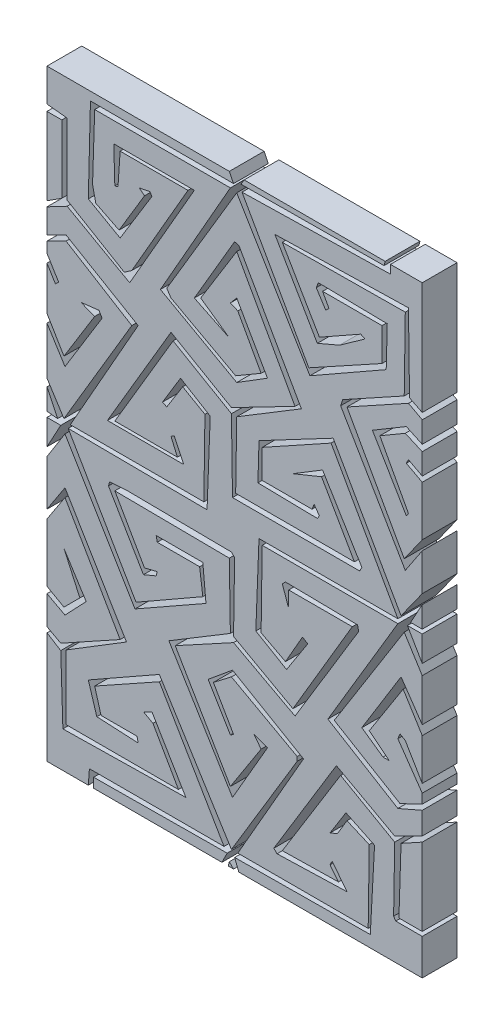
SolidWorks part; units mm, degrees
ref_plane "Front Plane" through (0, 0, 0) normal (0, 0, 1) x (1, 0, 0)
ref_plane "Top Plane" through (0, 0, 0) normal (0, 1, 0) x (1, 0, 0)
ref_plane "Right Plane" through (0, 0, 0) normal (1, 0, 0) x (0, 0, -1)
sketch "Sketch1" plane through (0, 0, 0) normal (0, 0, 1) x (1, 0, 0)
  line L0 (13.9275, -25.2817) -> (13.8361, -25.6475)
  line L1 (13.8361, -25.6475) -> (14.2933, -25.6475)
  line L2 (14.2933, -25.6475) -> (13.9275, -25.2817)
  line L3 (2.2224, -25.6475) -> (13.2874, -25.6475)
  line L4 (13.2874, -25.6475) -> (13.7446, -24.733)
  line L5 (13.7446, -24.733) -> (2.2224, -24.8245)
  line L6 (2.2224, -24.8245) -> (2.2224, -25.6475)
  line L7 (30.5707, -15.497) -> (28.7418, -16.5029)
  line L8 (28.7418, -16.5029) -> (28.5589, -22.1725)
  line L9 (28.5589, -22.1725) -> (30.5707, -22.1725)
  line L10 (30.5707, -22.1725) -> (30.5707, -15.497)
  line L11 (-0.2467, -5.1635) -> (-1.8012, -7.5411)
  line L12 (-1.8012, -7.5411) -> (-1.8012, -12.5707)
  line L13 (-1.8012, -12.5707) -> (-0.3381, -13.3937)
  line L14 (-0.3381, -13.3937) -> (1.0336, -12.022)
  line L15 (1.0336, -12.022) -> (-0.3381, -9.0043)
  line L16 (-0.3381, -9.0043) -> (1.5823, -12.022)
  line L17 (1.5823, -12.022) -> (-0.2467, -13.9424)
  line L18 (-0.2467, -13.9424) -> (-1.8012, -13.1194)
  line L19 (-1.8012, -13.1194) -> (-1.8012, -15.5884)
  line L20 (-1.8012, -15.5884) -> (-0.6124, -16.2285)
  line L21 (-0.6124, -16.2285) -> (4.5085, -13.3937)
  line L22 (4.5085, -13.3937) -> (-0.2467, -5.1635)
  line L23 (29.0161, -0.5912) -> (22.9807, -10.1931)
  line L24 (22.9807, -10.1931) -> (28.6503, -13.5766)
  line L25 (28.6503, -13.5766) -> (30.5707, -12.6621)
  line L26 (30.5707, -12.6621) -> (30.5707, -11.8391)
  line L27 (30.5707, -11.8391) -> (28.4675, -8.8214)
  line L28 (28.4675, -8.8214) -> (28.6503, -8.3642)
  line L29 (28.6503, -8.3642) -> (29.1076, -8.6385)
  line L30 (29.1076, -8.6385) -> (30.5707, -11.1075)
  line L31 (30.5707, -11.1075) -> (30.5707, -7.5411)
  line L32 (30.5707, -7.5411) -> (28.9247, -4.8892)
  line L33 (28.9247, -4.8892) -> (25.9984, -9.4615)
  line L34 (25.9984, -9.4615) -> (27.7359, -10.8332)
  line L35 (27.7359, -10.8332) -> (27.1872, -10.8332)
  line L36 (27.1872, -10.8332) -> (25.3583, -9.553)
  line L37 (25.3583, -9.553) -> (28.7418, -4.0662)
  line L38 (28.7418, -4.0662) -> (30.5707, -6.7181)
  line L39 (30.5707, -6.7181) -> (30.5707, -3.0603)
  line L40 (30.5707, -3.0603) -> (29.0161, -0.5912)
  line L41 (29.2905, 0.0489) -> (30.5707, -2.1458)
  line L42 (30.5707, -2.1458) -> (30.5707, 0.0489)
  line L43 (30.5707, 0.0489) -> (29.2905, 0.0489)
  line L44 (-0.6124, 0.0489) -> (-1.8012, 0.0489)
  line L45 (-1.8012, 0.0489) -> (-1.8012, -2.1458)
  line L46 (-1.8012, -2.1458) -> (-0.6124, 0.0489)
  line L47 (30.5707, 2.2436) -> (29.5648, 0.4147)
  line L48 (29.5648, 0.4147) -> (30.5707, 0.4147)
  line L49 (30.5707, 0.4147) -> (30.5707, 2.2436)
  line L50 (-1.8012, 2.335) -> (-1.8012, 0.5061)
  line L51 (-1.8012, 0.5061) -> (-0.8868, 0.4147)
  line L52 (-0.8868, 0.4147) -> (-1.8012, 2.335)
  line L53 (-0.1552, 14.0402) -> (-1.8012, 13.2171)
  line L54 (-1.8012, 13.2171) -> (-1.8012, 12.3027)
  line L55 (-1.8012, 12.3027) -> (-0.7953, 10.6567)
  line L56 (-0.7953, 10.6567) -> (-1.0697, 10.3823)
  line L57 (-1.0697, 10.3823) -> (-1.8012, 11.5711)
  line L58 (-1.8012, 11.5711) -> (-1.8012, 7.8218)
  line L59 (-1.8012, 7.8218) -> (-0.3381, 5.3528)
  line L60 (-0.3381, 5.3528) -> (2.3138, 9.6507)
  line L61 (2.3138, 9.6507) -> (1.125, 10.108)
  line L62 (1.125, 10.108) -> (2.6796, 10.2909)
  line L63 (2.6796, 10.2909) -> (2.954, 9.8336)
  line L64 (2.954, 9.8336) -> (-0.2467, 4.6212)
  line L65 (-0.2467, 4.6212) -> (-1.8012, 7.0903)
  line L66 (-1.8012, 7.0903) -> (-1.8012, 2.9752)
  line L67 (-1.8012, 2.9752) -> (-0.3381, 0.689)
  line L68 (-0.3381, 0.689) -> (5.5145, 10.5652)
  line L69 (5.5145, 10.5652) -> (-0.1552, 14.0402)
  line L70 (29.3819, 16.6921) -> (24.078, 13.7658)
  line L71 (24.078, 13.7658) -> (29.0161, 4.8955)
  line L72 (29.0161, 4.8955) -> (30.5707, 7.0903)
  line L73 (30.5707, 7.0903) -> (30.5707, 11.3882)
  line L74 (30.5707, 11.3882) -> (29.199, 12.1198)
  line L75 (29.199, 12.1198) -> (29.3819, 12.4856)
  line L76 (29.3819, 12.4856) -> (30.5707, 11.8455)
  line L77 (30.5707, 11.8455) -> (30.5707, 13.6744)
  line L78 (30.5707, 13.6744) -> (29.1076, 14.3145)
  line L79 (29.1076, 14.3145) -> (26.9129, 13.0343)
  line L80 (26.9129, 13.0343) -> (29.3819, 8.4619)
  line L81 (29.3819, 8.4619) -> (29.199, 8.1876)
  line L82 (29.199, 8.1876) -> (26.2727, 13.1257)
  line L83 (26.2727, 13.1257) -> (29.199, 14.8632)
  line L84 (29.199, 14.8632) -> (30.5707, 14.2231)
  line L85 (30.5707, 14.2231) -> (30.5707, 16.052)
  line L86 (30.5707, 16.052) -> (29.3819, 16.6921)
  line L87 (-0.521, 22.9104) -> (-1.8012, 22.9104)
  line L88 (-1.8012, 22.9104) -> (-1.8012, 16.2349)
  line L89 (-1.8012, 16.2349) -> (-0.521, 17.0579)
  line L90 (-0.521, 17.0579) -> (-0.521, 22.9104)
  line L91 (14.9334, 25.8367) -> (27.2787, 25.9282)
  line L92 (27.2787, 25.9282) -> (27.3701, 26.294)
  line L93 (27.3701, 26.294) -> (15.2077, 26.294)
  line L94 (15.2077, 26.294) -> (14.9334, 25.8367)
  line L95 (-1.8012, 26.294) -> (-1.8012, 23.4591)
  line L96 (-1.8012, 23.4591) -> (-0.0638, 23.2762)
  line L97 (-0.0638, 23.2762) -> (-0.0638, 17.1493)
  line L98 (-0.0638, 17.1493) -> (4.8743, 14.2231)
  line L99 (4.8743, 14.2231) -> (5.5145, 14.6803)
  line L100 (5.5145, 14.6803) -> (10.3611, 23.0933)
  line L101 (10.3611, 23.0933) -> (4.5085, 23.0933)
  line L102 (4.5085, 23.0933) -> (4.3256, 20.35)
  line L103 (4.3256, 20.35) -> (4.0513, 20.2585)
  line L104 (4.0513, 20.2585) -> (3.9599, 23.3677)
  line L105 (3.9599, 23.3677) -> (10.9098, 23.3677)
  line L106 (10.9098, 23.3677) -> (5.3316, 13.6744)
  line L107 (5.3316, 13.6744) -> (-0.0638, 16.6921)
  line L108 (-0.0638, 16.6921) -> (-1.8012, 15.7776)
  line L109 (-1.8012, 15.7776) -> (-1.8012, 13.6744)
  line L110 (-1.8012, 13.6744) -> (-0.1552, 14.4974)
  line L111 (-0.1552, 14.4974) -> (6.0631, 10.8395)
  line L112 (6.0631, 10.8395) -> (0.2106, 0.5061)
  line L113 (0.2106, 0.5061) -> (11.7328, 0.5061)
  line L114 (11.7328, 0.5061) -> (11.8242, 7.0903)
  line L115 (11.8242, 7.0903) -> (9.9039, 8.1876)
  line L116 (9.9039, 8.1876) -> (8.5322, 5.9929)
  line L117 (8.5322, 5.9929) -> (8.1664, 6.1758)
  line L118 (8.1664, 6.1758) -> (9.721, 8.7363)
  line L119 (9.721, 8.7363) -> (12.2815, 7.1817)
  line L120 (12.2815, 7.1817) -> (12.0071, 0.0489)
  line L121 (12.0071, 0.0489) -> (0.0277, 0.1403)
  line L122 (0.0277, 0.1403) -> (5.8802, -9.9187)
  line L123 (5.8802, -9.9187) -> (11.6413, -6.6267)
  line L124 (11.6413, -6.6267) -> (11.367, -4.5234)
  line L125 (11.367, -4.5234) -> (7.7092, -4.5234)
  line L126 (7.7092, -4.5234) -> (7.6177, -4.0662)
  line L127 (7.6177, -4.0662) -> (11.6413, -4.0662)
  line L128 (11.6413, -4.0662) -> (11.9157, -6.9925)
  line L129 (11.9157, -6.9925) -> (5.7888, -10.4674)
  line L130 (5.7888, -10.4674) -> (-0.2467, -0.4083)
  line L131 (-0.2467, -0.4083) -> (-1.8012, -2.8774)
  line L132 (-1.8012, -2.8774) -> (-1.8012, -6.8096)
  line L133 (-1.8012, -6.8096) -> (-0.2467, -4.432)
  line L134 (-0.2467, -4.432) -> (5.0572, -13.3023)
  line L135 (5.0572, -13.3023) -> (-0.1552, -16.5029)
  line L136 (-0.1552, -16.5029) -> (-0.1552, -22.0811)
  line L137 (-0.1552, -22.0811) -> (9.5381, -22.0811)
  line L138 (9.5381, -22.0811) -> (7.3434, -18.2404)
  line L139 (7.3434, -18.2404) -> (6.5204, -17.7831)
  line L140 (6.5204, -17.7831) -> (7.2519, -17.4173)
  line L141 (7.2519, -17.4173) -> (10.1782, -22.3554)
  line L142 (10.1782, -22.3554) -> (-0.4296, -22.5383)
  line L143 (-0.4296, -22.5383) -> (-0.6124, -16.7772)
  line L144 (-0.6124, -16.7772) -> (-1.8012, -16.0456)
  line L145 (-1.8012, -16.0456) -> (-1.8012, -25.6475)
  line L146 (-1.8012, -25.6475) -> (1.7652, -25.6475)
  line L147 (1.7652, -25.6475) -> (1.8566, -24.3672)
  line L148 (1.8566, -24.3672) -> (13.4703, -24.3672)
  line L149 (13.4703, -24.3672) -> (7.8921, -14.8568)
  line L150 (7.8921, -14.8568) -> (2.3138, -17.966)
  line L151 (2.3138, -17.966) -> (2.8625, -19.8864)
  line L152 (2.8625, -19.8864) -> (5.9717, -19.8864)
  line L153 (5.9717, -19.8864) -> (6.0631, -20.3436)
  line L154 (6.0631, -20.3436) -> (2.4967, -20.1607)
  line L155 (2.4967, -20.1607) -> (1.7652, -17.7831)
  line L156 (1.7652, -17.7831) -> (7.8921, -14.3082)
  line L157 (7.8921, -14.3082) -> (14.1104, -24.2758)
  line L158 (14.1104, -24.2758) -> (19.7801, -14.8568)
  line L159 (19.7801, -14.8568) -> (19.7801, -14.4911)
  line L160 (19.7801, -14.4911) -> (14.1104, -11.3819)
  line L161 (14.1104, -11.3819) -> (12.5558, -12.5707)
  line L162 (12.5558, -12.5707) -> (14.2933, -15.5884)
  line L163 (14.2933, -15.5884) -> (14.0189, -15.7713)
  line L164 (14.0189, -15.7713) -> (12.0986, -12.5707)
  line L165 (12.0986, -12.5707) -> (14.2018, -10.8332)
  line L166 (14.2018, -10.8332) -> (20.3287, -14.3996)
  line L167 (20.3287, -14.3996) -> (14.6591, -24.2758)
  line L168 (14.6591, -24.2758) -> (25.907, -24.2758)
  line L169 (25.907, -24.2758) -> (25.9984, -17.966)
  line L170 (25.9984, -17.966) -> (24.078, -17.143)
  line L171 (24.078, -17.143) -> (23.255, -18.5147)
  line L172 (23.255, -18.5147) -> (22.6149, -18.789)
  line L173 (22.6149, -18.789) -> (23.9866, -16.5943)
  line L174 (23.9866, -16.5943) -> (26.4556, -17.7831)
  line L175 (26.4556, -17.7831) -> (26.0898, -24.6416)
  line L176 (26.0898, -24.6416) -> (14.3847, -24.733)
  line L177 (14.3847, -24.733) -> (14.7505, -25.6475)
  line L178 (14.7505, -25.6475) -> (30.5707, -25.6475)
  line L179 (30.5707, -25.6475) -> (30.5707, -22.5383)
  line L180 (30.5707, -22.5383) -> (28.2846, -22.5383)
  line L181 (28.2846, -22.5383) -> (28.1017, -22.264)
  line L182 (28.1017, -22.264) -> (28.1931, -16.6858)
  line L183 (28.1931, -16.6858) -> (23.5294, -14.0338)
  line L184 (23.5294, -14.0338) -> (18.4998, -22.1725)
  line L185 (18.4998, -22.1725) -> (23.3465, -22.0811)
  line L186 (23.3465, -22.0811) -> (22.6149, -21.1666)
  line L187 (22.6149, -21.1666) -> (22.7978, -20.8008)
  line L188 (22.7978, -20.8008) -> (24.078, -22.4469)
  line L189 (24.078, -22.4469) -> (18.0426, -22.6298)
  line L190 (18.0426, -22.6298) -> (17.7682, -22.3554)
  line L191 (17.7682, -22.3554) -> (23.1636, -13.4851)
  line L192 (23.1636, -13.4851) -> (28.1931, -16.2285)
  line L193 (28.1931, -16.2285) -> (30.5707, -15.0397)
  line L194 (30.5707, -15.0397) -> (30.5707, -13.1194)
  line L195 (30.5707, -13.1194) -> (28.4675, -14.0338)
  line L196 (28.4675, -14.0338) -> (22.432, -10.376)
  line L197 (22.432, -10.376) -> (28.4675, -0.2254)
  line L198 (28.4675, -0.2254) -> (16.7623, -0.2254)
  line L199 (16.7623, -0.2254) -> (16.6709, -6.8096)
  line L200 (16.6709, -6.8096) -> (18.7742, -7.9069)
  line L201 (18.7742, -7.9069) -> (20.2373, -5.3464)
  line L202 (20.2373, -5.3464) -> (20.6945, -5.6208)
  line L203 (20.6945, -5.6208) -> (18.8656, -8.4556)
  line L204 (18.8656, -8.4556) -> (16.2137, -6.901)
  line L205 (16.2137, -6.901) -> (16.488, 0.1403)
  line L206 (16.488, 0.1403) -> (28.4675, 0.1403)
  line L207 (28.4675, 0.1403) -> (22.7063, 10.3823)
  line L208 (22.7063, 10.3823) -> (16.7623, 7.0903)
  line L209 (16.7623, 7.0903) -> (16.7623, 4.6212)
  line L210 (16.7623, 4.6212) -> (21.0603, 4.6212)
  line L211 (21.0603, 4.6212) -> (21.2432, 5.0784)
  line L212 (21.2432, 5.0784) -> (21.7004, 4.4383)
  line L213 (21.7004, 4.4383) -> (21.5175, 4.164)
  line L214 (21.5175, 4.164) -> (16.3966, 4.2554)
  line L215 (16.3966, 4.2554) -> (16.488, 7.456)
  line L216 (16.488, 7.456) -> (22.8892, 10.8395)
  line L217 (22.8892, 10.8395) -> (28.7418, 0.5061)
  line L218 (28.7418, 0.5061) -> (30.5707, 3.0666)
  line L219 (30.5707, 3.0666) -> (30.5707, 6.2672)
  line L220 (30.5707, 6.2672) -> (29.1076, 4.0725)
  line L221 (29.1076, 4.0725) -> (23.5294, 13.5829)
  line L222 (23.5294, 13.5829) -> (23.7122, 14.1316)
  line L223 (23.7122, 14.1316) -> (29.0161, 17.0579)
  line L224 (29.0161, 17.0579) -> (29.1076, 23.3677)
  line L225 (29.1076, 23.3677) -> (18.4998, 23.2762)
  line L226 (18.4998, 23.2762) -> (21.7004, 17.7895)
  line L227 (21.7004, 17.7895) -> (25.2668, 19.8013)
  line L228 (25.2668, 19.8013) -> (25.6326, 19.6184)
  line L229 (25.6326, 19.6184) -> (23.4379, 18.0638)
  line L230 (23.4379, 18.0638) -> (21.5175, 17.2408)
  line L231 (21.5175, 17.2408) -> (17.8597, 23.5506)
  line L232 (17.8597, 23.5506) -> (29.3819, 23.8249)
  line L233 (29.3819, 23.8249) -> (29.4734, 17.1493)
  line L234 (29.4734, 17.1493) -> (30.5707, 16.6007)
  line L235 (30.5707, 16.6007) -> (30.5707, 26.294)
  line L236 (30.5707, 26.294) -> (27.8273, 26.294)
  line L237 (27.8273, 26.294) -> (27.8273, 25.5624)
  line L238 (27.8273, 25.5624) -> (15.0249, 25.288)
  line L239 (15.0249, 25.288) -> (20.786, 15.0461)
  line L240 (20.786, 15.0461) -> (27.0958, 18.521)
  line L241 (27.0958, 18.521) -> (27.0958, 21.3559)
  line L242 (27.0958, 21.3559) -> (21.9748, 21.3559)
  line L243 (21.9748, 21.3559) -> (22.5234, 20.35)
  line L244 (22.5234, 20.35) -> (22.2491, 20.0756)
  line L245 (22.2491, 20.0756) -> (21.4261, 21.3559)
  line L246 (21.4261, 21.3559) -> (21.609, 21.8131)
  line L247 (21.609, 21.8131) -> (27.553, 21.7216)
  line L248 (27.553, 21.7216) -> (27.4615, 18.2467)
  line L249 (27.4615, 18.2467) -> (20.8774, 14.4974)
  line L250 (20.8774, 14.4974) -> (14.5676, 25.0137)
  line L251 (14.5676, 25.0137) -> (8.5322, 14.8632)
  line L252 (8.5322, 14.8632) -> (8.898, 14.3145)
  line L253 (8.898, 14.3145) -> (14.4762, 11.2968)
  line L254 (14.4762, 11.2968) -> (16.6709, 12.577)
  line L255 (16.6709, 12.577) -> (14.6591, 16.2349)
  line L256 (14.6591, 16.2349) -> (14.0189, 16.5092)
  line L257 (14.0189, 16.5092) -> (14.5676, 17.1493)
  line L258 (14.5676, 17.1493) -> (17.2196, 12.4856)
  line L259 (17.2196, 12.4856) -> (14.5676, 10.8395)
  line L260 (14.5676, 10.8395) -> (7.9835, 14.4974)
  line L261 (7.9835, 14.4974) -> (14.0189, 25.1052)
  line L262 (14.0189, 25.1052) -> (2.3138, 25.1052)
  line L263 (2.3138, 25.1052) -> (2.1309, 19.4355)
  line L264 (2.1309, 19.4355) -> (2.4053, 18.1552)
  line L265 (2.4053, 18.1552) -> (4.4171, 17.1493)
  line L266 (4.4171, 17.1493) -> (6.6118, 20.8072)
  line L267 (6.6118, 20.8072) -> (6.1546, 21.173)
  line L268 (6.1546, 21.173) -> (7.069, 21.3559)
  line L269 (7.069, 21.3559) -> (7.2519, 21.0815)
  line L270 (7.2519, 21.0815) -> (4.5085, 16.6007)
  line L271 (4.5085, 16.6007) -> (1.7652, 18.1552)
  line L272 (1.7652, 18.1552) -> (1.948, 25.5624)
  line L273 (1.948, 25.5624) -> (14.2933, 25.5624)
  line L274 (14.2933, 25.5624) -> (13.9275, 26.294)
  line L275 (13.9275, 26.294) -> (-1.8012, 26.294)
  line L276 (24.9925, -2.0544) -> (25.0839, -2.5116)
  line L277 (25.0839, -2.5116) -> (19.5972, -11.5648)
  line L278 (19.5972, -11.5648) -> (14.2933, -8.7299)
  line L279 (14.2933, -8.7299) -> (9.2637, -11.4733)
  line L280 (9.2637, -11.4733) -> (14.0189, -19.612)
  line L281 (14.0189, -19.612) -> (16.6709, -15.497)
  line L282 (16.6709, -15.497) -> (16.0308, -14.6739)
  line L283 (16.0308, -14.6739) -> (17.2196, -15.1312)
  line L284 (17.2196, -15.1312) -> (14.2018, -20.3436)
  line L285 (14.2018, -20.3436) -> (8.7151, -11.3819)
  line L286 (8.7151, -11.3819) -> (14.0189, -8.1813)
  line L287 (14.0189, -8.1813) -> (13.9275, -2.603)
  line L288 (13.9275, -2.603) -> (4.0513, -2.5116)
  line L289 (4.0513, -2.5116) -> (6.6118, -6.9925)
  line L290 (6.6118, -6.9925) -> (7.7092, -6.7181)
  line L291 (7.7092, -6.7181) -> (7.6177, -7.0839)
  line L292 (7.6177, -7.0839) -> (6.5204, -7.5411)
  line L293 (6.5204, -7.5411) -> (3.5026, -2.4202)
  line L294 (3.5026, -2.4202) -> (3.5941, -2.0544)
  line L295 (3.5941, -2.0544) -> (5.1487, -1.9629)
  line L296 (5.1487, -1.9629) -> (14.1104, -2.0544)
  line L297 (14.1104, -2.0544) -> (14.3847, -2.3287)
  line L298 (14.3847, -2.3287) -> (14.2933, -8.2727)
  line L299 (14.2933, -8.2727) -> (19.4143, -11.1075)
  line L300 (19.4143, -11.1075) -> (24.5353, -2.4202)
  line L301 (24.5353, -2.4202) -> (19.0485, -2.4202)
  line L302 (19.0485, -2.4202) -> (19.0485, -3.7918)
  line L303 (19.0485, -3.7918) -> (18.4998, -2.2373)
  line L304 (18.4998, -2.2373) -> (18.7742, -1.9629)
  line L305 (18.7742, -1.9629) -> (24.9925, -2.0544)
  line L306 (14.3847, 21.2644) -> (14.7505, 21.173)
  line L307 (14.7505, 21.173) -> (20.1458, 11.6626)
  line L308 (20.1458, 11.6626) -> (14.5676, 8.2791)
  line L309 (14.5676, 8.2791) -> (14.4762, 2.5179)
  line L310 (14.4762, 2.5179) -> (24.7182, 2.5179)
  line L311 (24.7182, 2.5179) -> (21.8833, 7.456)
  line L312 (21.8833, 7.456) -> (19.4143, 6.4501)
  line L313 (19.4143, 6.4501) -> (21.9748, 8.0047)
  line L314 (21.9748, 8.0047) -> (25.3583, 2.4265)
  line L315 (25.3583, 2.4265) -> (25.1754, 2.0607)
  line L316 (25.1754, 2.0607) -> (14.2018, 2.0607)
  line L317 (14.2018, 2.0607) -> (14.1104, 8.2791)
  line L318 (14.1104, 8.2791) -> (9.0809, 11.2053)
  line L319 (9.0809, 11.2053) -> (4.0513, 2.7008)
  line L320 (4.0513, 2.7008) -> (9.4466, 2.7008)
  line L321 (9.4466, 2.7008) -> (8.898, 3.9811)
  line L322 (8.898, 3.9811) -> (9.1723, 4.164)
  line L323 (9.1723, 4.164) -> (9.9953, 2.4265)
  line L324 (9.9953, 2.4265) -> (3.4112, 2.4265)
  line L325 (3.4112, 2.4265) -> (8.898, 11.754)
  line L326 (8.898, 11.754) -> (14.1104, 8.7363)
  line L327 (14.1104, 8.7363) -> (19.5972, 11.5711)
  line L328 (19.5972, 11.5711) -> (14.5676, 20.6243)
  line L329 (14.5676, 20.6243) -> (11.4585, 15.5948)
  line L330 (11.4585, 15.5948) -> (13.9275, 13.8573)
  line L331 (13.9275, 13.8573) -> (10.9098, 15.3204)
  line L332 (10.9098, 15.3204) -> (14.3847, 21.2644)
extrude "Boss-Extrude1" add sketch "Sketch1" along normal blind 3
